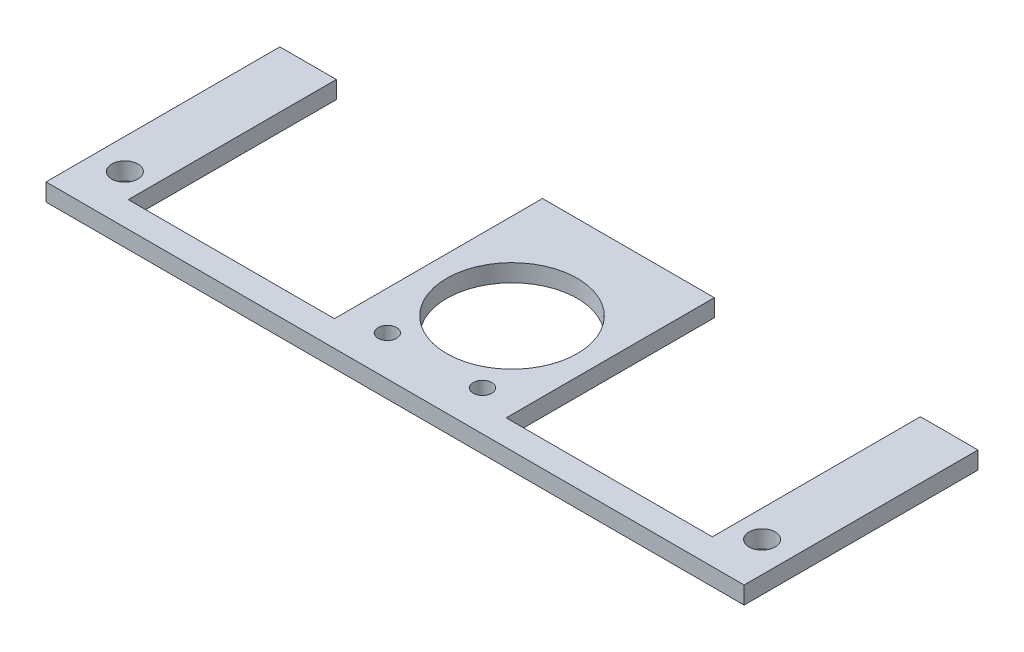
SolidWorks part; units mm, degrees
ref_plane "Front Plane" through (0, 0, 0) normal (0, 0, 1) x (1, 0, 0)
ref_plane "Top Plane" through (0, 0, 0) normal (0, 1, 0) x (1, 0, 0)
ref_plane "Right Plane" through (0, 0, 0) normal (1, 0, 0) x (0, 0, -1)
sketch "Sketch1" plane through (0, 0, 0) normal (0, 1, 0) x (1, 0, 0)
  line L1 (0, 0) -> (101.6, 0)
  line L2 (0, 0) -> (0, 34.036)
  line L3 (0, 34.036) -> (101.6, 34.036)
  line L4 (101.6, 0) -> (101.6, 34.036)
  dimension "D1" = 101.6
  dimension "D2" = 34.036
extrude "Boss-Extrude1" add sketch "Sketch1" along normal blind 2.54
sketch "Sketch2" plane through (0, 2.54, 0) normal (0, 1, 0) x (1, 0, 0)
  line L0 (50.8, 0) -> (50.8, 34.036)
  line L2 (0, 0) -> (101.6, 0) construction
  line L3 (101.6, 34.036) -> (0, 34.036) construction
  line L5 (0, 0) -> (4.43, 0)
  line L6 (0, 0) -> (0, 7.045)
  line L7 (0, 7.045) -> (4.43, 7.045)
  line L8 (4.43, 0) -> (4.43, 7.045)
  line L9 (101.6, 0) -> (97.17, 0)
  line L10 (101.6, 0) -> (101.6, 7.045)
  line L11 (101.6, 7.045) -> (97.17, 7.045)
  line L12 (97.17, 0) -> (97.17, 7.045)
  line L13 (0, 0) -> (43.875, 0)
  line L14 (0, 0) -> (0, 5.8)
  line L15 (0, 5.8) -> (43.875, 5.8)
  line L16 (43.875, 0) -> (43.875, 5.8)
  line L17 (101.6, 0) -> (57.725, 0)
  line L18 (101.6, 0) -> (101.6, 5.8)
  line L19 (101.6, 5.8) -> (57.725, 5.8)
  line L20 (57.725, 0) -> (57.725, 5.8)
  circle A0 centre (50.8, 17.018) radius 9.5
  dimension "D1" = 4.43
  dimension "D5" = 43.875
  dimension "D2" = 7.045
  dimension "D3" = 4.43
  dimension "D4" = 7.045
  dimension "D6" = 5.8
  dimension "D7" = 43.875
  dimension "D8" = 5.8
sketch "Sketch7" plane through (0, 2.54, 0) normal (0, 1, 0) x (1, 0, 0)
  line L1 (38.2202, 18.75) -> (38.2202, 34.036)
  line L2 (101.6, 34.036) -> (0, 34.036) construction
  line L3 (38.2202, 34.036) -> (8.2202, 34.036)
  line L4 (38.2202, 34.036) -> (38.2202, 3.75)
  line L5 (38.2202, 3.75) -> (8.2202, 3.75)
  line L6 (8.2202, 34.036) -> (8.2202, 3.75)
  dimension "D1" = 30
extrude "Cut-Extrude2" cut sketch "Sketch7" against normal blind 2.54 contours L3 L6 L5 L4 L1
pattern_linear "LPattern1" count 2 spacing 55 along (1, 0, 0) of "Cut-Extrude2"
hole_wizard "Tap Drill for #6-32 Tap1" positions "Sketch8" profile "Sketch9" hole size "#6-32" standard "ANSI Inch" end condition through all
sketch "Sketch8" plane through (0, 2.54, 0) normal (0, 1, 0) x (1, 0, 0)
  point P0 (43.875, 5.8)
  point P3 (57.725, 5.8)
sketch "Sketch9" plane through (43.875, 2.54, -5.8) normal (1, 0, 0) x (0, 0, 1)
  line L0 (0, 0) -> (0, 2.54)
  line L1 (0, 2.54) -> (1.3525, 2.54)
  line L2 (1.3525, 2.54) -> (1.3525, 0)
  line L5 (1.3525, 0) -> (0, 0)
  line L11 (0, -6.35) -> (0, 107.95) construction
  dimension "Thru Hole Dia." = 2.7051
  dimension "Thru Hole Depth" = 2.54
sketch "Sketch11" plane through (0, 2.54, 0) normal (0, 1, 0) x (1, 0, 0)
  circle A0 centre (4.43, 7.045) radius 1.905
  circle A1 centre (97.17, 7.045) radius 1.905
extrude "Cut-Extrude3" cut sketch "Sketch2" against normal blind 2.54 contours A0
extrude "Cut-Extrude5" cut sketch "Sketch11" against normal blind 2.54
